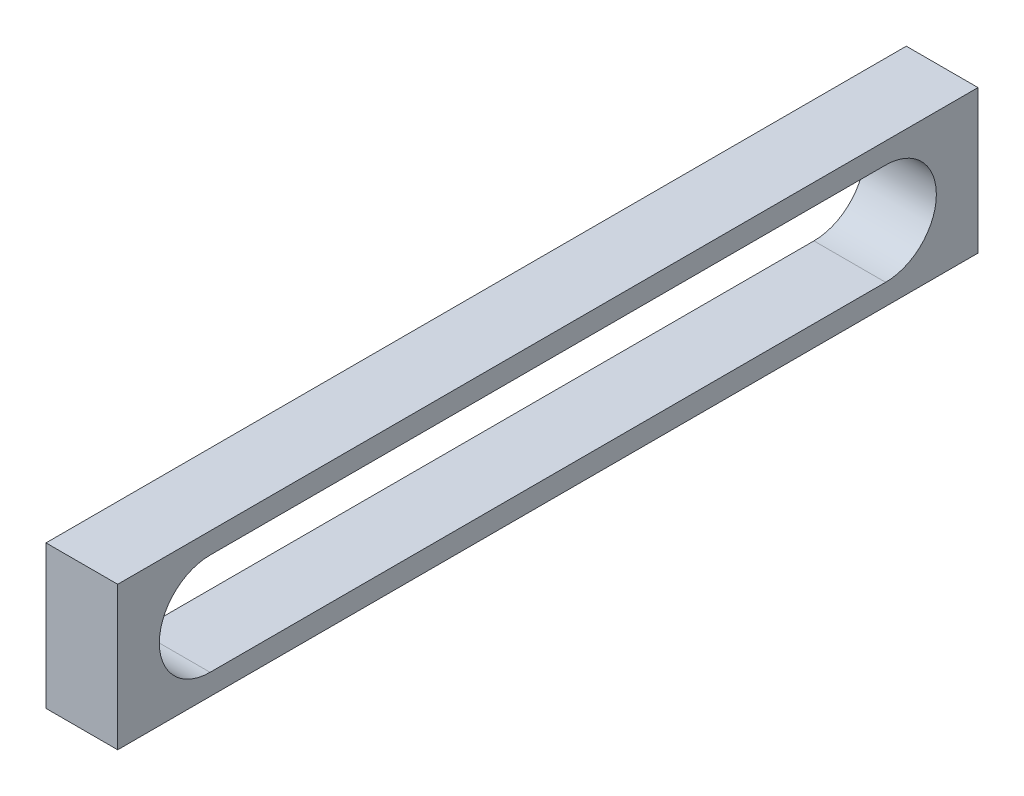
SolidWorks part; units mm, degrees
ref_plane "Front Plane" through (0, 0, 0) normal (0, 0, 1) x (1, 0, 0)
ref_plane "Top Plane" through (0, 0, 0) normal (0, 1, 0) x (1, 0, 0)
ref_plane "Right Plane" through (0, 0, 0) normal (1, 0, 0) x (0, 0, -1)
sketch "Sketch1" plane through (0, 0, 0) normal (1, 0, 0) x (0, 0, -1)
  line L1 (0, 0) -> (-152.4, 0)
  line L2 (0, 0) -> (0, 25.4)
  line L3 (0, 25.4) -> (-152.4, 25.4)
  line L4 (-152.4, 0) -> (-152.4, 25.4)
  dimension "D1" = 152.4
  dimension "D2" = 25.4
extrude "Boss-Extrude1" add sketch "Sketch1" along normal blind 12.7
sketch "Sketch3" plane through (12.7, 2.361, 0) normal (1, 0, 0) x (0, 0, -1)
  line L0 (-136.0334, 10.339) -> (-16.3666, 10.339) construction
  line L1 (-136.0334, 19.3299) -> (-16.3666, 19.3299)
  line L2 (-136.0334, 1.3482) -> (-16.3666, 1.3482)
  line L3 (-152.4, -2.361) -> (0, 23.039) construction
  arc A0 (-136.0334, 19.3299) -> (-136.0334, 1.3482) centre (-136.0334, 10.339) ccw
  arc A1 (-16.3666, 1.3482) -> (-16.3666, 19.3299) centre (-16.3666, 10.339) ccw
  point P2 (-76.2, 10.339)
  point P11 (-76.2, 10.339)
  point P12 (-16.3666, 10.339)
  point P13 (0, 0)
  point P14 (0, 0)
  point P15 (0, 0)
extrude "Cut-Extrude2" cut sketch "Sketch3" against normal up to next
